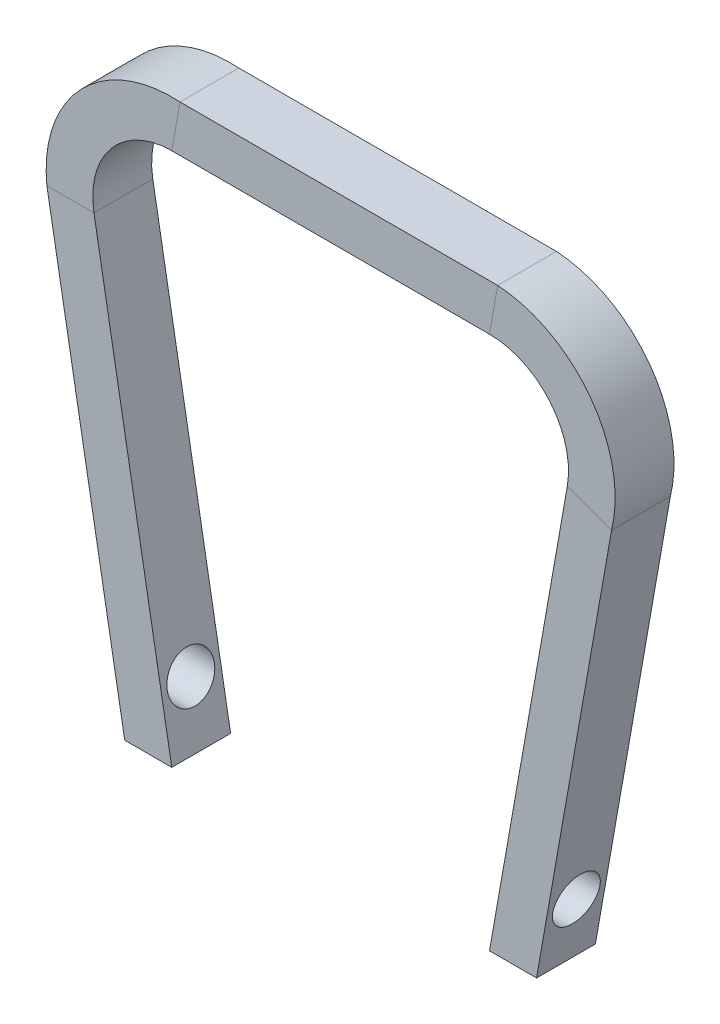
SolidWorks part; units mm, degrees
ref_plane "Front Plane" through (0, 0, 0) normal (0, 0, 1) x (1, 0, 0)
ref_plane "Top Plane" through (0, 0, 0) normal (0, 1, 0) x (1, 0, 0)
ref_plane "Right Plane" through (0, 0, 0) normal (1, 0, 0) x (0, 0, -1)
sketch "Sketch1" plane through (0, 0, 0) normal (0, 0, 1) x (1, 0, 0)
  line L0 (0, 0) -> (-16.7951, 95.25)
  line L1 (0, 0) -> (0, 220.035) construction
  line L2 (0, 115.2657) -> (68.58, 115.2657)
  line L3 (34.29, 115.2657) -> (34.29, 177.6593) construction
  line L4 (68.58, 0) -> (85.3751, 95.25)
  arc A0 (-16.7951, 95.25) -> (0, 115.2657) centre (0, 98.2114) cw
  arc A1 (85.3751, 95.25) -> (68.58, 115.2657) centre (68.58, 98.2114) ccw
  dimension "D1" = 95.25
  dimension "D2" = 10
  dimension "D3" = 34.29
sketch "Sketch2" plane through (0, 0, 0) normal (0, 1, 0) x (1, 0, 0)
  line L0 (0, 0) -> (-16.7951, 0) construction
  line L1 (-10.16, -6.35) -> (0, -6.35)
  line L2 (-10.16, -6.35) -> (-10.16, 6.35)
  line L3 (-10.16, 6.35) -> (0, 6.35)
  line L4 (0, -6.35) -> (0, 6.35)
  line L5 (-10.16, -6.35) -> (0, 6.35) construction
  line L6 (-10.16, 6.35) -> (0, -6.35) construction
  point P0 (-5.08, 0)
  dimension "D1" = 10.16
  dimension "D2" = 12.7
sweep "Sweep2" add profiles "Sketch2" path "Sketch1"
sketch "Sketch3" plane through (0, 0, 0) normal (0, 1, 0) x (1, 0, 0)
  line L1 (68.58, -6.35) -> (78.74, -6.35)
  line L2 (68.58, -6.35) -> (68.58, 6.35)
  line L3 (68.58, 6.35) -> (78.74, 6.35)
  line L4 (78.74, -6.35) -> (78.74, 6.35)
  line L5 (68.58, -6.35) -> (78.74, 6.35) construction
  line L6 (68.58, 6.35) -> (78.74, -6.35) construction
  point P0 (73.66, 0)
  dimension "D1" = 68.58
  dimension "D2" = 12.7
  dimension "D3" = 10.16
extrude "Cut-Extrude1" cut sketch "Sketch3" against normal blind 5.08
sketch "Sketch5" plane through (0, 0, 0) normal (1, 0, 0) x (0, 0, -1)
  circle A0 centre (0, 12.7) radius 5.0929
  dimension "D1" = 10.1858
  dimension "D2" = 12.7
extrude "Cut-Extrude2" cut sketch "Sketch5" against normal mid plane 254
ref_plane "Plane1" through (36.0543, 0, 0) normal (1, 0, 0) x (0, 0, -1)
ref_plane "Plane2" through (2.3743, 13.4653, 0) normal (0.1736, 0.9848, 0) x (0, 0, -1)
ref_plane "Plane3" through (-0.3064, 1.7375, 0) normal (0.1736, -0.9848, 0) x (0, 0, 1)
